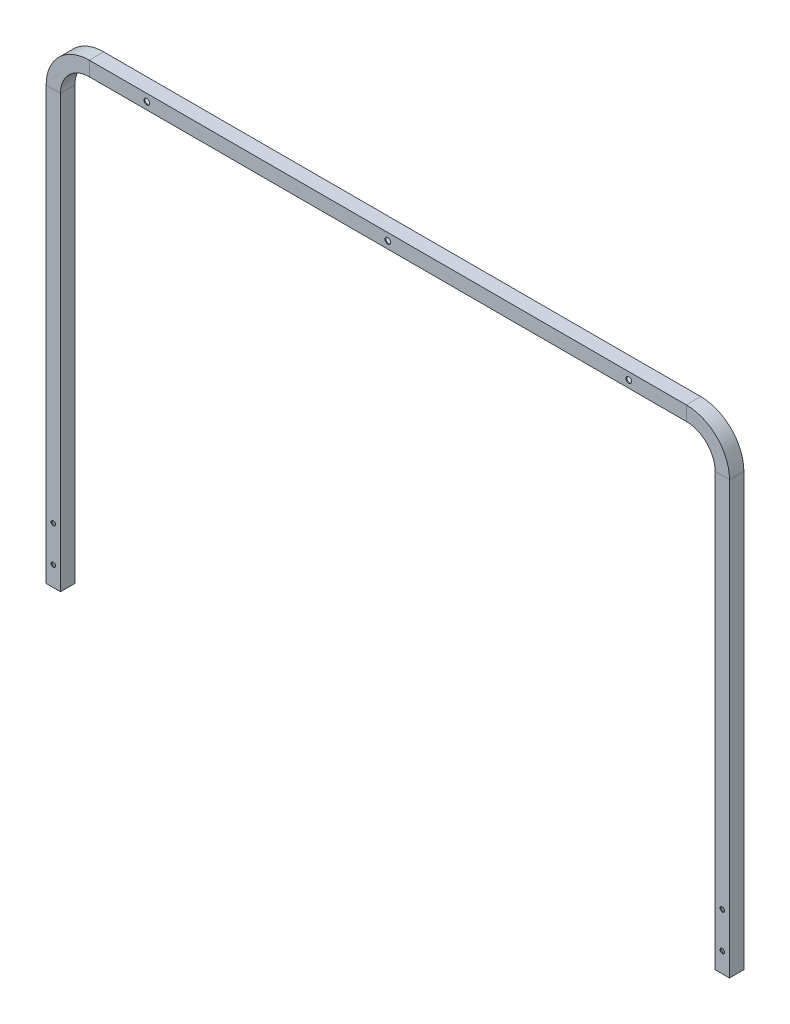
SolidWorks part; units mm, degrees
ref_plane "Front Plane" through (0, 0, 0) normal (0, 0, 1) x (1, 0, 0)
ref_plane "Top Plane" through (0, 0, 0) normal (0, 1, 0) x (1, 0, 0)
ref_plane "Right Plane" through (0, 0, 0) normal (1, 0, 0) x (0, 0, -1)
sketch "Sketch1" plane through (0, 0, 0) normal (0, 0, 1) x (1, 0, 0)
  line L0 (0, 0) -> (0, 600)
  line L1 (50, 650) -> (880, 650)
  line L2 (930, 600) -> (930, 0)
  arc A0 (930, 600) -> (880, 650) centre (880, 600) ccw
  arc A1 (0, 600) -> (50, 650) centre (50, 600) cw
  dimension "D3" = 50
  dimension "D1" = 930
  dimension "D2" = 650
other "Al tube square AL TUBE 0.75 SQR X 0.065 WALL(1)"
ref_plane "Plane1" through (0, 0, 0) normal (0, 1, 0) x (-1, 0, 0)
sketch "Sketch15" plane through (0, 0, 0) normal (0, 1, 0) x (-1, 0, 0)
  line L0 (-8.8, -8.8) -> (-8.8, 8.8)
  line L1 (8.8, 8.8) -> (-8.8, 8.8)
  line L2 (8.8, 8.8) -> (8.8, -8.8)
  line L3 (-8.8, -8.8) -> (8.8, -8.8)
  line L4 (-10, -10) -> (10, -10)
  line L5 (-10, -10) -> (-10, 10)
  line L6 (10, 10) -> (-10, 10)
  line L7 (10, 10) -> (10, -10)
  line L8 (0, -8.8) -> (0, -10) construction
  line L9 (0, -8.8) -> (0, 8.8) construction
  line L10 (0, 8.8) -> (0, 10) construction
  line L11 (10, 0) -> (8.8, 0) construction
  line L12 (8.8, 0) -> (-8.8, 0) construction
  line L13 (-8.8, 0) -> (-10, 0) construction
  point P14 (0, 0)
  point P17 (0, 0)
  dimension "Thickness" = 1.2
  dimension "V_leg" = 20
  dimension "H_leg" = 20
sketch "Sketch16" plane through (0, 0, 10) normal (0, 0, 1) x (1, 0, 0)
  line L0 (50, 650) -> (880, 650) construction
  line L1 (50, 640) -> (50, 660) construction
  line L2 (880, 640) -> (880, 660) construction
  line L3 (10, 600) -> (10, 0) construction
  circle A0 centre (130, 650) radius 4
  circle A1 centre (800, 650) radius 4
  circle A2 centre (465, 650) radius 4
  dimension "D1" = 8
  dimension "D3" = 335
  dimension "D4" = 335
  dimension "D2" = 120
extrude "Cut-Extrude1" cut sketch "Sketch16" against normal through all
sketch "Sketch17" plane through (0, 0, -10) normal (0, 0, -1) x (-1, 0, 0)
  circle A0 centre (-930, 27.5) radius 5 construction
  circle A1 centre (-930, 77.5) radius 5 construction
  circle A2 centre (-930, 27.5) radius 5 construction
  circle A3 centre (-930, 77.5) radius 5 construction
  circle A4 centre (0, 27.5) radius 5 construction
  circle A5 centre (0, 77.5) radius 5 construction
  circle A6 centre (0, 27.5) radius 5 construction
  circle A7 centre (0, 77.5) radius 5 construction
  circle A8 centre (-930, 27.5) radius 3.125
  circle A9 centre (-930, 77.5) radius 3.125
  circle A10 centre (0, 77.5) radius 3.125
  circle A11 centre (0, 27.5) radius 3.125
  dimension "D1" = 6.25
extrude "Cut-Extrude2" cut sketch "Sketch17" against normal through all
